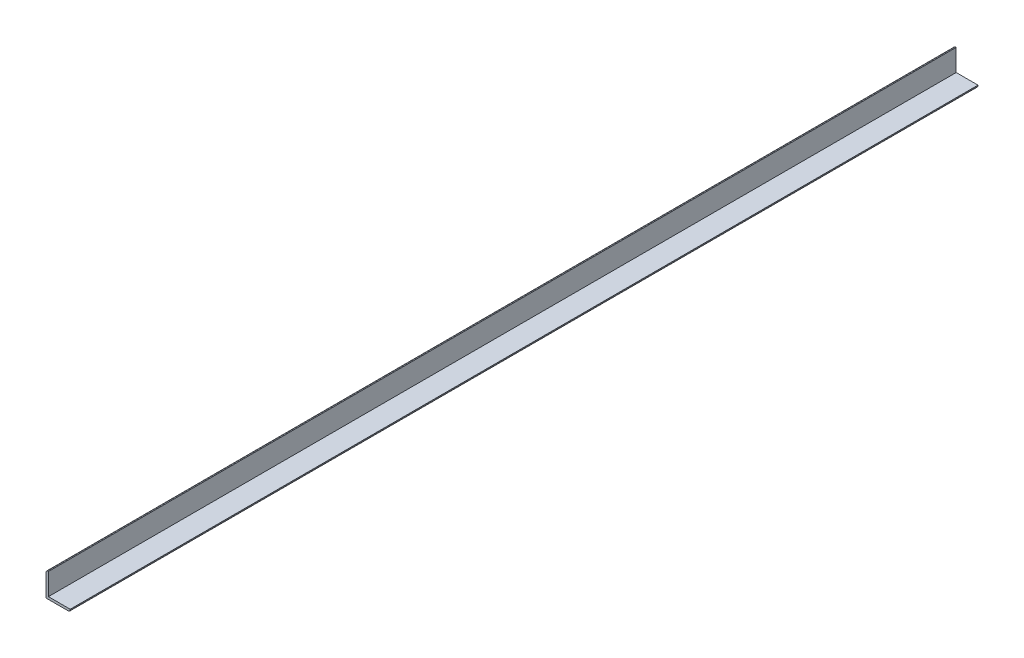
SolidWorks part; units mm, degrees
ref_plane "Спереди" through (0, 0, 0) normal (0, 0, 1) x (1, 0, 0)
ref_plane "Сверху" through (0, 0, 0) normal (0, 1, 0) x (1, 0, 0)
ref_plane "Справа" through (0, 0, 0) normal (1, 0, 0) x (0, 0, -1)
sketch "Эскиз1" plane through (0, 0, 0) normal (0, 0, 1) x (1, 0, 0)
  line L0 (0, 0) -> (37, 0)
  line L1 (40, 3) -> (40, 4)
  line L2 (4, 4) -> (4, 40)
  line L3 (4, 40) -> (3, 40)
  line L4 (0, 37) -> (0, 0)
  line L5 (4, 4) -> (40, 4)
  arc A0 (37, 0) -> (40, 3) centre (37, 3) ccw
  arc A1 (3, 40) -> (0, 37) centre (3, 37) ccw
  point P11 (0, 40)
  dimension "D1" = 4
  dimension "D3" = 3
  dimension "D2" = 36
extrude "Бобышка-Вытянуть1" add sketch "Эскиз1" along normal up to surface (1500 mm away)
